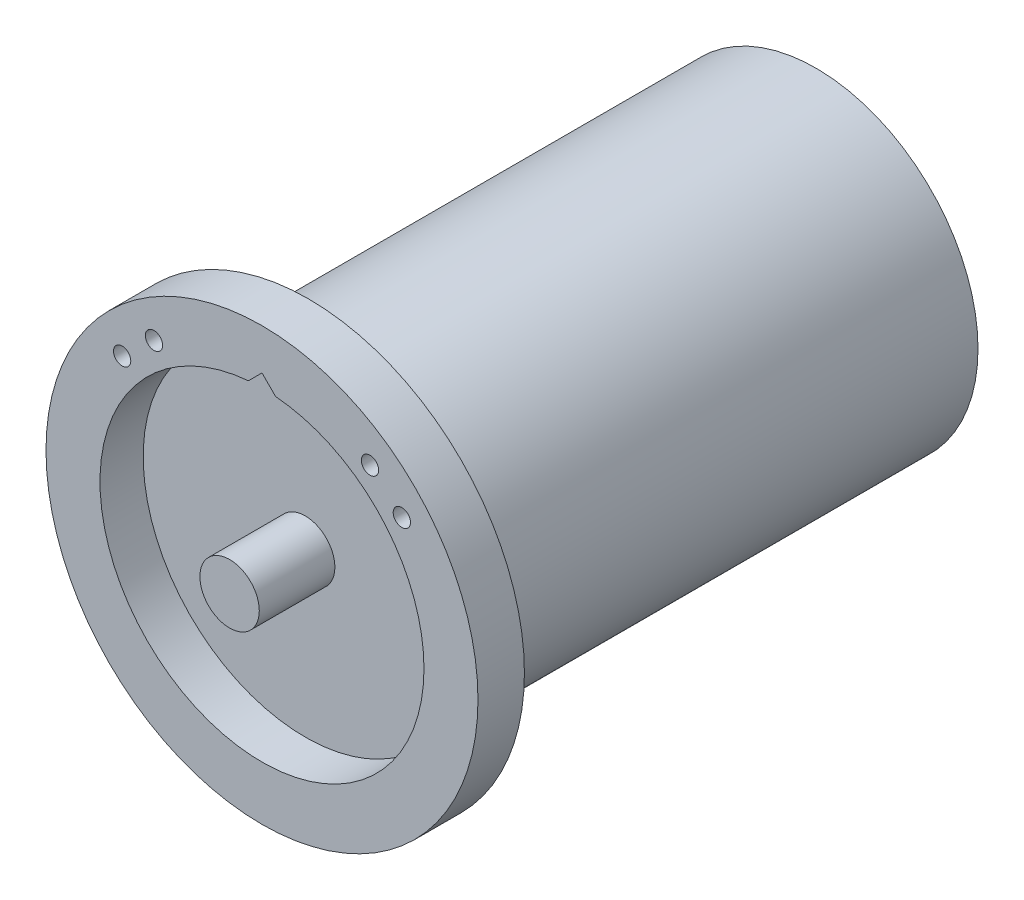
SolidWorks part; units mm, degrees
material "1350 合金"
ref_plane "前视基准面" through (0, 0, 0) normal (0, 0, 1) x (1, 0, 0)
ref_plane "上视基准面" through (0, 0, 0) normal (0, 1, 0) x (1, 0, 0)
ref_plane "右视基准面" through (0, 0, 0) normal (1, 0, 0) x (0, 0, -1)
sketch "草图2" plane through (0, 0, 0) normal (0, 0, 1) x (1, 0, 0)
  circle A0 centre (0, 0) radius 15.5
  dimension "D1" = 31
extrude "凸台-拉伸1" add sketch "草图2" along normal blind 2
sketch "草图3" plane through (0, 0, 0) normal (0, 0, -1) x (-1, 0, 0)
  circle A0 centre (0, 0) radius 15
  dimension "D1" = 30
extrude "凸台-拉伸2" add sketch "草图3" along normal blind 45
sketch "草图4" plane through (0, 0, 2) normal (0, 0, 1) x (1, 0, 0)
  circle A0 centre (0, 0) radius 20
  dimension "D1" = 40
extrude "凸台-拉伸3" add sketch "草图4" along normal blind 4.3
sketch "草图5" plane through (0, 0, 6.3) normal (0, 0, 1) x (1, 0, 0)
  circle A0 centre (0, 0) radius 15
  dimension "D1" = 30
extrude "切除-拉伸2" cut sketch "草图5" against normal blind 4
sketch "草图6" plane through (0, 0, 2.3) normal (0, 0, 1) x (1, 0, 0)
  circle A0 centre (0, 0) radius 2.75
  dimension "D1" = 5.5
extrude "凸台-拉伸4" add sketch "草图6" along normal blind 7
sketch "草图7" plane through (0, 0, 6.3) normal (0, 0, 1) x (1, 0, 0)
  line L0 (0, -1000) -> (0, 49000) construction
  circle A0 centre (0, 0) radius 17.05 construction
  circle A1 centre (-10, 13.8095) radius 0.8
  circle A2 centre (10, 13.8095) radius 0.8
  circle A3 centre (-12.95, 11.0905) radius 0.8
  circle A4 centre (12.95, 11.0905) radius 0.8
  dimension "D1" = 34.1
  dimension "D2" = 20
  dimension "D3" = 1.6
  dimension "D4" = 25.9
  dimension "D5" = 1.6
extrude "切除-拉伸3" cut sketch "草图7" against normal blind 7
cosmetic thread "装饰螺纹线1" parameters "D2"=2
cosmetic thread "装饰螺纹线2" parameters "D2"=2
cosmetic thread "装饰螺纹线3" parameters "D2"=2
cosmetic thread "装饰螺纹线4" parameters "D2"=2
sketch "草图9" plane through (0, 0, 6.3) normal (0, 0, 1) x (1, 0, 0)
  line L0 (0, 0) -> (0, 10.55) construction
  line L1 (0, 10.55) -> (0, 13.378) construction
  line L6 (-2.8284, 13.378) -> (0, 16.2064)
  line L7 (-2.8284, 13.378) -> (0, 10.5496)
  line L8 (0, 16.2064) -> (2.8284, 13.378)
  line L9 (0, 10.5496) -> (2.8284, 13.378)
  line L10 (-2.8284, 13.378) -> (2.8284, 13.378) construction
  line L11 (0, 16.2064) -> (0, 10.5496) construction
  dimension "D1" = 10.55
  dimension "D2" = 2.828
  dimension "D3" = 4
  dimension "D4" = 4
extrude "切除-拉伸4" cut sketch "草图9" against normal blind 2
sketch "草图10" plane through (0, 0, -45) normal (0, 0, -1) x (-1, 0, 0)
  line L0 (0, 0) -> (0, 13) construction
  line L1 (0, 0) -> (11.2583, 6.5) construction
  circle A0 centre (0, 0) radius 13 construction
  circle A1 centre (11.2583, 6.5) radius 1.6
  circle A2 centre (0, 13) radius 1.6
  circle A3 centre (11.2583, -6.5) radius 1.6
  circle A4 centre (0, -13) radius 1.6
  circle A5 centre (-11.2583, -6.5) radius 1.6
  circle A6 centre (-11.2583, 6.5) radius 1.6
  point P6 (0, 0)
  point P7 (0, 0)
  point P18 (-12.0226, 8.0546)
  point P20 (0, 0)
  dimension "D1" = 26
  dimension "D2" = 3.2
  dimension "D4" = 60
  dimension "D5" = 13
  dimension "D3" = 6
extrude "切除-拉伸5" cut sketch "草图10" against normal blind 10
cosmetic thread "装饰螺纹线5" parameters "D1"=5, "D2"=4
cosmetic thread "装饰螺纹线6" parameters "D1"=5, "D2"=4
cosmetic thread "装饰螺纹线7" parameters "D1"=5, "D2"=4
cosmetic thread "装饰螺纹线8" parameters "D1"=5, "D2"=4
cosmetic thread "装饰螺纹线9" parameters "D1"=5, "D2"=4
cosmetic thread "装饰螺纹线10" parameters "D1"=5, "D2"=4
